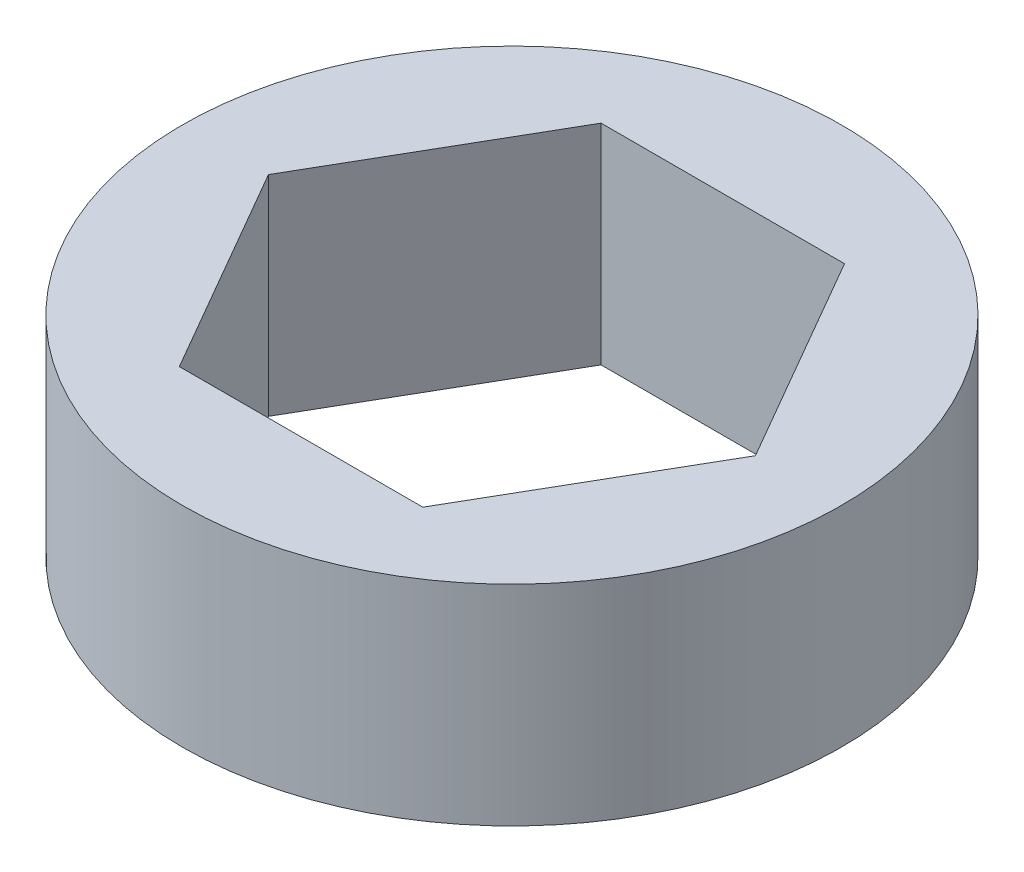
SolidWorks part; units mm, degrees
ref_plane "Front Plane" through (0, 0, 0) normal (0, 0, 1) x (1, 0, 0)
ref_plane "Top Plane" through (0, 0, 0) normal (0, 1, 0) x (1, 0, 0)
ref_plane "Right Plane" through (0, 0, 0) normal (1, 0, 0) x (0, 0, -1)
sketch "Sketch1" plane through (0, 0, 0) normal (0, 1, 0) x (1, 0, 0)
  line L1 (7.3837, 0) -> (3.6918, 6.3944)
  line L2 (3.6918, 6.3944) -> (-3.6918, 6.3944)
  line L3 (-3.6918, 6.3944) -> (-7.3837, 0)
  line L4 (-7.3837, 0) -> (-3.6918, -6.3945)
  line L5 (-3.6918, -6.3945) -> (3.6918, -6.3944)
  line L6 (3.6918, -6.3944) -> (7.3837, 0)
  circle A0 centre (0, 0) radius 6.3944 construction
  circle A1 centre (0, 0) radius 9.9949
  dimension "D1" = 12.7889
  dimension "D2" = 19.9898
extrude "Boss-Extrude1" add sketch "Sketch1" along normal blind 6.35
